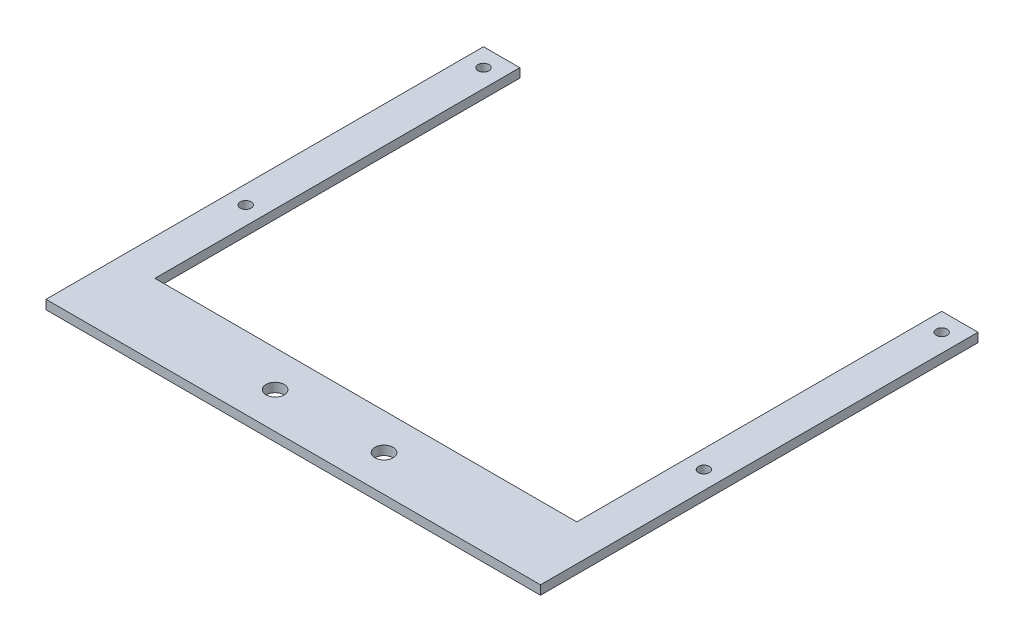
SolidWorks part; units mm, degrees
material "1060 Alloy"
ref_plane "Front Plane" through (0, 0, 0) normal (0, 0, 1) x (1, 0, 0)
ref_plane "Top Plane" through (0, 0, 0) normal (0, 1, 0) x (1, 0, 0)
ref_plane "Right Plane" through (0, 0, 0) normal (1, 0, 0) x (0, 0, -1)
sketch "Sketch3" plane through (0, 0, 0) normal (0, 1, 0) x (1, 0, 0)
  line L0 (-63.1, 0) -> (-63.1, 65.5) construction
  line L1 (63.1, 0) -> (-63.1, 0) construction
  line L2 (-63.1, 65.5) -> (-63.1, 70.5) construction
  line L3 (0, 0) -> (0, 65.5) construction
  line L4 (0, 65.5) -> (0, 70.5) construction
  line L5 (-68.1, 70.5) -> (-58.1, 70.5)
  line L6 (-58.1, 70.5) -> (-58.1, -30)
  line L7 (0, -40) -> (-15, -40) construction
  line L8 (-68.1, 70.5) -> (-68.1, -50)
  line L9 (-68.1, -50) -> (68.1, -50)
  line L10 (-58.1, -30) -> (58.1, -30)
  line L11 (63.1, 65.5) -> (63.1, 70.5) construction
  line L12 (63.1, 0) -> (63.1, 65.5) construction
  line L13 (68.1, 70.5) -> (68.1, -50)
  line L14 (0, -30) -> (0, -50) construction
  line L15 (58.1, 70.5) -> (58.1, -30)
  line L16 (68.1, 70.5) -> (58.1, 70.5)
  circle A0 centre (-63.1, 65.5) radius 1.5
  circle A1 centre (-63.1, 0) radius 1.5
  circle A2 centre (63.1, 0) radius 1.5
  circle A3 centre (63.1, 65.5) radius 1.5
  circle A4 centre (-15, -40) radius 2.5
  circle A5 centre (15, -40) radius 2.5
  point P12 (-63.1, 70.5)
  point P16 (-63.1, 0)
  point P25 (0, -30)
  point P26 (0, -50)
  dimension "D3" = 3
  dimension "D4" = 3
  dimension "D10" = 5
  dimension "D1" = 65.5
  dimension "D2" = 63.1
  dimension "D5" = 5
  dimension "D6" = 100.5
  dimension "D7" = 15
  dimension "D8" = 10
  dimension "D9" = 120.5
extrude "Boss-Extrude2" add sketch "Sketch3" along normal blind 2.5
